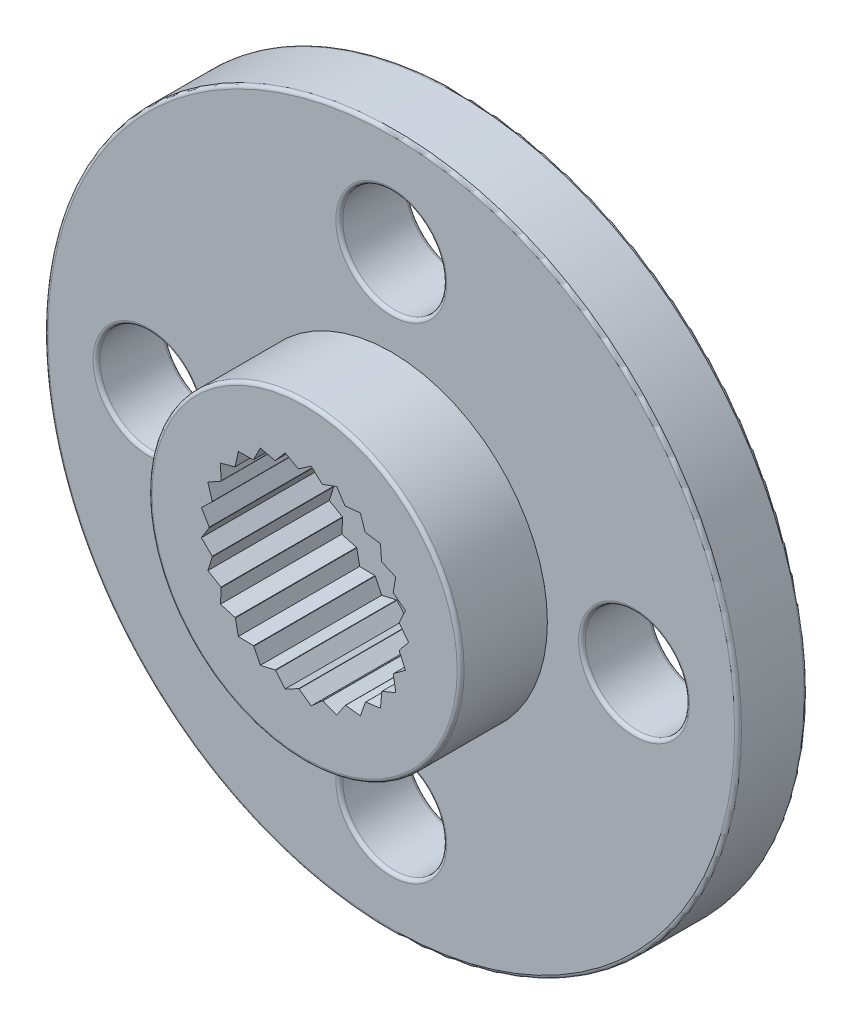
SolidWorks part; units mm, degrees
material "1060 Alloy"
ref_plane "Front Plane" through (0, 0, 0) normal (0, 0, 1) x (1, 0, 0)
ref_plane "Top Plane" through (0, 0, 0) normal (0, 1, 0) x (1, 0, 0)
ref_plane "Right Plane" through (0, 0, 0) normal (1, 0, 0) x (0, 0, -1)
sketch "Sketch1" plane through (0, 0, 0) normal (0, 0, 1) x (1, 0, 0)
  circle A0 centre (0, 0) radius 10
extrude "Boss-Extrude1" add sketch "Sketch1" along normal blind 2
sketch "Sketch2" plane through (0, 0, 2) normal (0, 0, 1) x (1, 0, 0)
  circle A0 centre (0, 0) radius 4.5
extrude "Boss-Extrude2" add sketch "Sketch2" along normal blind 2.5
sketch "Sketch3" plane through (0, 0, 4.5) normal (0, 0, 1) x (1, 0, 0)
  circle A0 centre (0, 0) radius 2.75
extrude "Cut-Extrude1" cut sketch "Sketch3" against normal blind 3.5
sketch "Sketch4" plane through (0, 0, 1) normal (0, 0, 1) x (1, 0, 0)
  circle A0 centre (0, 0) radius 1.5
extrude "Cut-Extrude2" cut sketch "Sketch4" against normal through all
sketch "Sketch5" plane through (0, 0, 4.5) normal (0, 0, 1) x (1, 0, 0)
  line L1 (-2.6565, 0.6821) -> (-2.6823, 0.6062)
  line L3 (-2.75, 0) -> (-2.9763, 0.376)
  line L4 (-2.9763, 0.376) -> (-2.6565, 0.6821)
  line L5 (-2.6823, 0.6062) -> (-2.75, 0)
  circle A2 centre (0, 0) radius 2.75 construction
extrude "Cut-Extrude3" cut sketch "Sketch5" against normal blind 3.5 contours L5 L3 L4 L1
pattern_circular "CirPattern1" count 25 over 360 about axis through (0, 0, 0) along (0, 0, 1) of "Cut-Extrude3"
sketch "Sketch6" plane through (0, 0, 2) normal (0, 0, 1) x (1, 0, 0)
  line L0 (0, 10) -> (0, -10) construction
  line L1 (0, -10) -> (10, 0) construction
  line L2 (10, 0) -> (-10, 0) construction
  line L3 (0, 0) -> (-7.0711, 7.0711) construction
  circle A0 centre (0, 0) radius 10 construction
  circle A1 centre (-7, 0) radius 1.5
  circle A2 centre (7, 0) radius 1.5
  circle A3 centre (0, 7) radius 1.5
  circle A4 centre (0, -7) radius 1.5
  dimension "D1" = 3
extrude "Cut-Extrude4" cut sketch "Sketch6" against normal through all
fillet "Fillet1" radius 0.1 1 edges at (5.5, 0, 2)
fillet "Fillet2" radius 0.1 12 edges at (10, 0, 0) (10, 0, 2) (1.5, 0, 0) (1.5, 0, 1) (4.5, 0, 4.5) (-1.5, 7, 0) (-1.5, 7, 2) (-5.5, 0, 0) (-5.5, 0, 2) (1.5, -7, 2) (1.5, -7, 0) (5.5, 0, 0)
